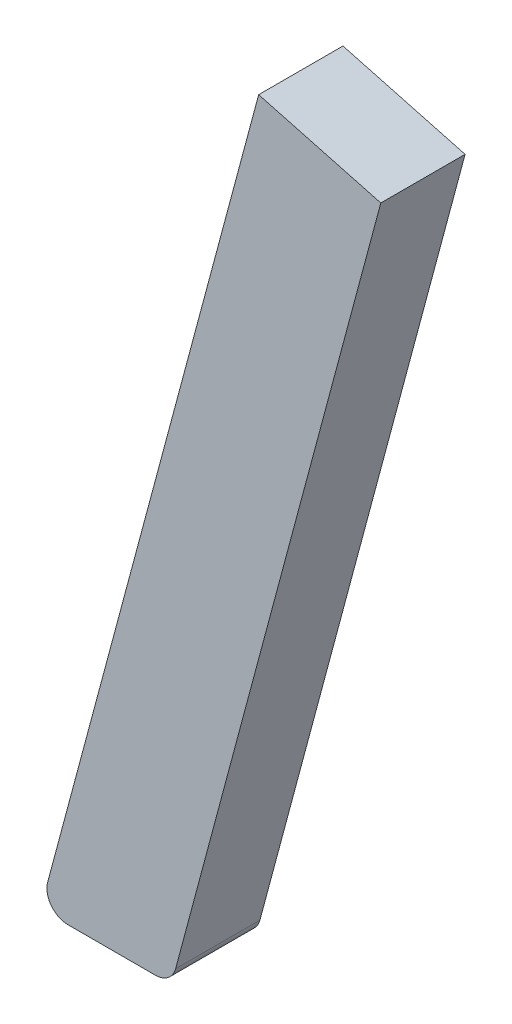
SolidWorks part; units mm, degrees
ref_plane "Plan de face" through (0, 0, 0) normal (0, 0, 1) x (1, 0, 0)
ref_plane "Plan de dessus" through (0, 0, 0) normal (0, 1, 0) x (1, 0, 0)
ref_plane "Plan de droite" through (0, 0, 0) normal (1, 0, 0) x (0, 0, -1)
sketch "Esquisse1" plane through (0, 0, 0) normal (0, 0, 1) x (1, 0, 0)
  line L0 (0, 0) -> (31.0583, 0)
  line L1 (31.0583, 0) -> (80.7416, 185.4206)
  line L2 (80.7416, 185.4206) -> (51.7638, 193.1852)
  line L3 (51.7638, 193.1852) -> (0, 0)
  dimension "D1" = 30
  dimension "D2" = 75
  dimension "D3" = 90
  dimension "D4" = 200
extrude "Boss.-Extru.1" add sketch "Esquisse1" along normal blind 20
fillet "Congé1" radius 5 2 edges at (31.0583, 0, 10) (0, 0, 10)
